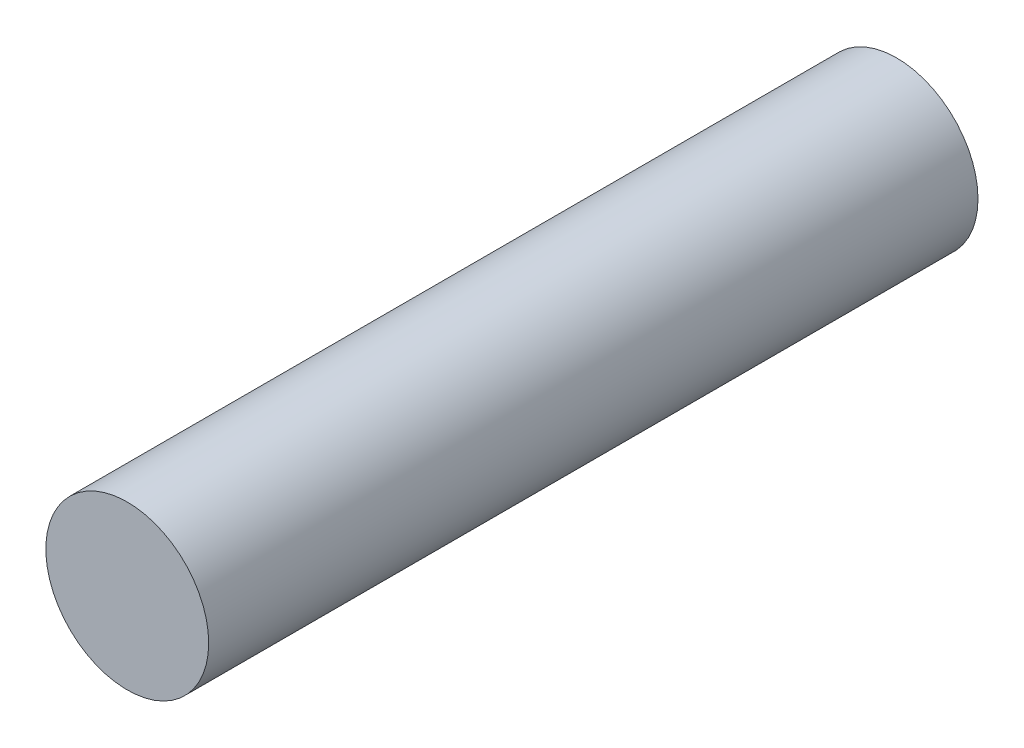
SolidWorks part; units mm, degrees
ref_plane "Front Plane" through (0, 0, 0) normal (0, 0, 1) x (1, 0, 0)
ref_plane "Top Plane" through (0, 0, 0) normal (0, 1, 0) x (1, 0, 0)
ref_plane "Right Plane" through (0, 0, 0) normal (1, 0, 0) x (0, 0, -1)
sketch "Sketch1" plane through (0, 0, 0) normal (0, 0, 1) x (1, 0, 0)
  circle A0 centre (0, 0) radius 3.175
  dimension "D1" = 6.35
extrude "Boss-Extrude1" add sketch "Sketch1" along normal blind 30
